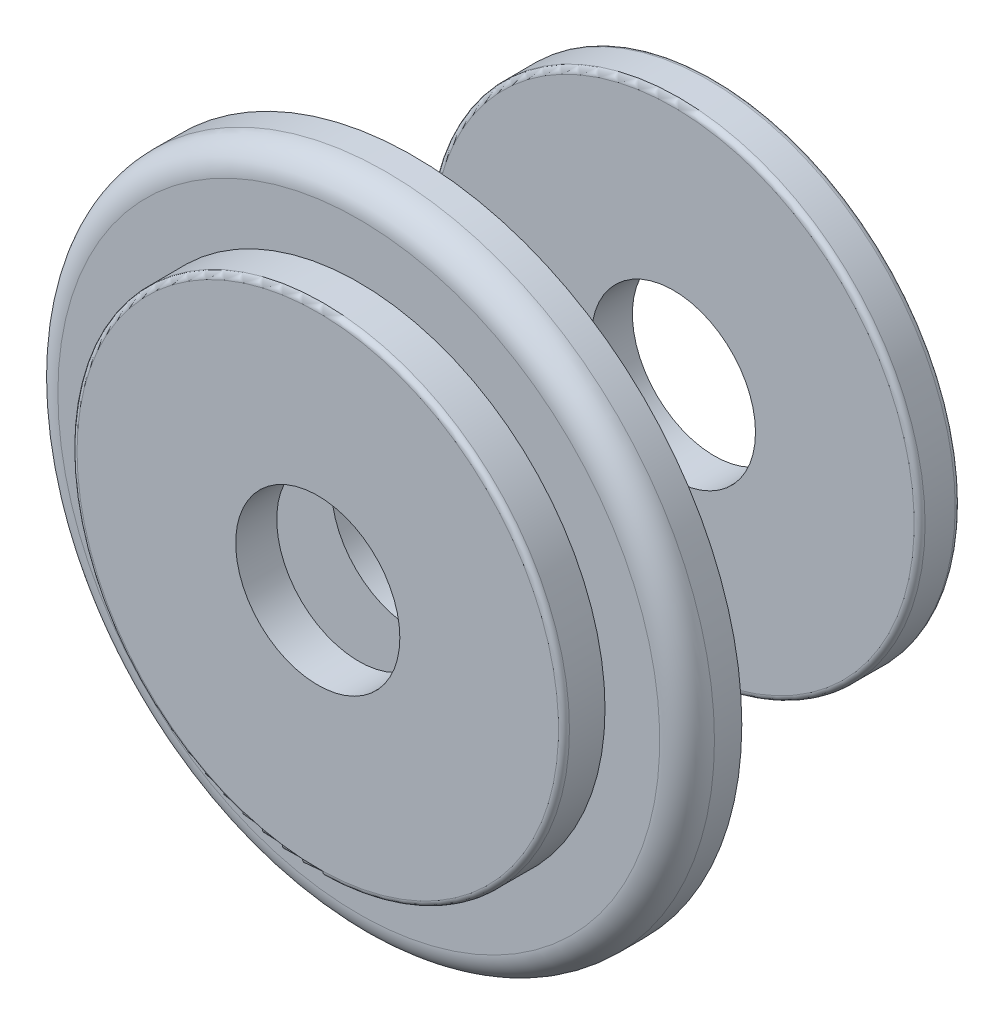
SolidWorks part; units mm, degrees
ref_plane "Plan de face" through (0, 0, 0) normal (0, 0, 1) x (1, 0, 0)
ref_plane "Plan de dessus" through (0, 0, 0) normal (0, 1, 0) x (1, 0, 0)
ref_plane "Plan de droite" through (0, 0, 0) normal (1, 0, 0) x (0, 0, -1)
sketch "Esquisse1" plane through (0, 0, 0) normal (1, 0, 0) x (0, 0, -1)
  line L0 (-20.5, 0) -> (23.8333, 0) construction
  line L1 (0, 18.4583) -> (0, -16.625) construction
  line L2 (4, 15.2083) -> (4, -20.375) construction
  line L3 (0, 1.5) -> (-0.75, 1.5)
  line L4 (-0.75, 1.5) -> (-0.75, 3)
  line L5 (-0.75, 3) -> (-1.75, 3)
  line L6 (-1.75, 3) -> (-1.75, 1.5)
  line L7 (-1.75, 1.5) -> (-2.5, 1.5)
  line L8 (-2.5, 1.5) -> (-2.5, 4.5)
  line L9 (-2.5, 4.5) -> (-1.75, 4.5)
  line L10 (-1.75, 4.5) -> (-1.75, 6)
  line L11 (-1.75, 6) -> (-0.75, 6)
  line L12 (-0.75, 6) -> (-0.75, 4.5)
  line L13 (-0.75, 4.5) -> (0, 4.5)
  line L14 (0, 4.5) -> (0, 1.5)
  line L15 (4, 1.5) -> (4, 4.5)
  line L16 (4, 4.5) -> (4.75, 4.5)
  line L17 (4.75, 4.5) -> (4.75, 1.5)
  line L18 (4.75, 1.5) -> (4, 1.5)
  dimension "D1" = 4
  dimension "D2" = 1.5
  dimension "D3" = 0.75
  dimension "D4" = 1
  dimension "D5" = 3
  dimension "D6" = 3
  dimension "D7" = 3
revolve "Révolution1" add sketch "Esquisse1" angle 360 about L0
fillet "Congé1" radius 0.5 1 edges at (6, 0, 1.75)
fillet "Congé2" radius 0.1 2 edges at (4.5, 0, 0) (4.5, 0, 2.5)
fillet "Congé3" radius 0.1 2 edges at (4.5, 0, -4.75) (4.5, 0, -4)
